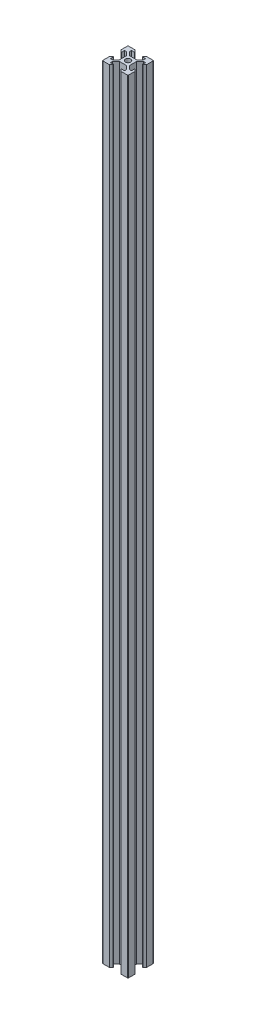
SolidWorks part; units mm, degrees
ref_plane "Front Plane" through (0, 0, 0) normal (0, 0, 1) x (1, 0, 0)
ref_plane "Top Plane" through (0, 0, 0) normal (0, 1, 0) x (1, 0, 0)
ref_plane "Right Plane" through (0, 0, 0) normal (1, 0, 0) x (0, 0, -1)
sketch "Sketch1" plane through (0, 0, 0) normal (1, 0, 0) x (0, 0, -1)
  line L0 (0, 0) -> (0, 609.6)
  dimension "D1" = 609.6
other "Vslot2020 2020(5)"
ref_plane "Plane5" through (0, 0, 0) normal (0, 1, 0) x (0, 0, 1)
sketch "Sketch2" plane through (0, 0, 0) normal (0, 1, 0) x (0, 0, 1)
  line L58 (13.9, 7.1491) -> (13.9, 12.8445)
  line L59 (13.9, 12.8445) -> (16.5585, 15.4922)
  line L60 (16.5585, 15.4922) -> (16.5507, 15.5)
  line L61 (16.5507, 15.5) -> (18.2, 15.5)
  line L62 (18.2, 15.5) -> (18.2, 13.12)
  line L63 (18.2, 13.12) -> (18.5344, 13.12)
  line L64 (18.5344, 13.12) -> (20, 14.58)
  line L65 (20, 14.58) -> (20, 19.5)
  line L66 (19.5, 20) -> (14.575, 20)
  line L67 (14.575, 20) -> (13.12, 18.545)
  line L68 (13.12, 18.545) -> (13.12, 18.2)
  line L69 (13.12, 18.2) -> (15.5, 18.2)
  line L70 (15.5, 18.2) -> (15.5, 16.555)
  line L71 (15.5, 16.555) -> (12.8341, 13.9)
  line L72 (12.8341, 13.9) -> (7.155, 13.9)
  line L73 (7.155, 13.9) -> (4.5, 16.555)
  line L74 (4.5, 16.555) -> (4.5, 18.2)
  line L75 (4.5, 18.2) -> (6.875, 18.2)
  line L76 (6.875, 18.2) -> (6.875, 18.545)
  line L77 (6.875, 18.545) -> (5.42, 20)
  line L78 (5.42, 20) -> (0.5, 20)
  line L79 (0, 19.5) -> (0, 14.58)
  line L80 (0, 14.58) -> (1.46, 13.12)
  line L81 (1.46, 13.12) -> (1.8, 13.12)
  line L82 (1.8, 13.12) -> (1.8, 15.5)
  line L83 (1.8, 15.5) -> (3.445, 15.5)
  line L84 (3.445, 15.5) -> (3.4393, 15.4943)
  line L85 (3.4393, 15.4943) -> (6.0943, 12.8393)
  line L86 (6.0943, 12.8393) -> (6.1, 12.845)
  line L87 (6.1, 12.845) -> (6.1, 7.1491)
  line L88 (6.1, 7.1491) -> (3.4393, 4.5)
  line L89 (3.4393, 4.5) -> (1.8, 4.5)
  line L90 (1.8, 4.5) -> (1.8, 6.88)
  line L91 (1.8, 6.88) -> (1.46, 6.88)
  line L92 (1.46, 6.88) -> (0, 5.42)
  line L93 (0, 5.42) -> (0, 0.5)
  line L94 (0.5, 0) -> (5.42, 0)
  line L95 (5.42, 0) -> (6.875, 1.455)
  line L96 (6.875, 1.455) -> (6.875, 1.8)
  line L97 (6.875, 1.8) -> (4.5, 1.8)
  line L98 (4.5, 1.8) -> (4.5, 3.4393)
  line L99 (4.5, 3.4393) -> (7.1583, 6.0861)
  line L100 (7.1583, 6.0861) -> (7.1445, 6.1)
  line L101 (7.1445, 6.1) -> (12.8546, 6.1)
  line L102 (12.8546, 6.1) -> (12.8412, 6.0865)
  line L103 (12.8412, 6.0865) -> (15.4997, 3.4375)
  line L104 (15.4997, 3.4375) -> (15.5, 3.4377)
  line L105 (15.5, 3.4377) -> (15.5, 1.8)
  line L106 (15.5, 1.8) -> (13.12, 1.8)
  line L107 (13.12, 1.8) -> (13.12, 1.455)
  line L108 (13.12, 1.455) -> (14.575, 0)
  line L109 (14.575, 0) -> (19.5, 0)
  line L110 (20, 0.5) -> (20, 5.42)
  line L111 (20, 5.42) -> (18.6069, 6.88)
  line L112 (18.6069, 6.88) -> (18.2, 6.88)
  line L113 (18.2, 6.88) -> (18.2, 4.5)
  line L114 (18.2, 4.5) -> (16.5585, 4.5)
  line L115 (16.5585, 4.5) -> (13.9, 7.1491)
  line L116 (13.9, 7.1491) -> (13.9, 12.8445)
  line L117 (13.9, 12.8445) -> (16.5585, 15.4922)
  line L118 (16.5585, 15.4922) -> (16.5507, 15.5)
  line L119 (16.5507, 15.5) -> (18.2, 15.5)
  line L120 (18.2, 15.5) -> (18.2, 13.12)
  line L121 (18.2, 13.12) -> (18.5344, 13.12)
  line L122 (18.5344, 13.12) -> (20, 14.58)
  line L123 (20, 14.58) -> (20, 19.5)
  line L124 (19.5, 20) -> (14.575, 20)
  line L125 (14.575, 20) -> (13.12, 18.545)
  line L126 (13.12, 18.545) -> (13.12, 18.2)
  line L127 (13.12, 18.2) -> (15.5, 18.2)
  line L128 (15.5, 18.2) -> (15.5, 16.555)
  line L129 (15.5, 16.555) -> (12.8341, 13.9)
  line L130 (12.8341, 13.9) -> (7.155, 13.9)
  line L131 (7.155, 13.9) -> (4.5, 16.555)
  line L132 (4.5, 16.555) -> (4.5, 18.2)
  line L133 (4.5, 18.2) -> (6.875, 18.2)
  line L134 (6.875, 18.2) -> (6.875, 18.545)
  line L135 (6.875, 18.545) -> (5.42, 20)
  line L136 (5.42, 20) -> (0.5, 20)
  line L137 (0, 19.5) -> (0, 14.58)
  line L138 (0, 14.58) -> (1.46, 13.12)
  line L139 (1.46, 13.12) -> (1.8, 13.12)
  line L140 (1.8, 13.12) -> (1.8, 15.5)
  line L141 (1.8, 15.5) -> (3.445, 15.5)
  line L142 (3.445, 15.5) -> (3.4393, 15.4943)
  line L143 (3.4393, 15.4943) -> (6.0943, 12.8393)
  line L144 (6.0943, 12.8393) -> (6.1, 12.845)
  line L145 (6.1, 12.845) -> (6.1, 7.1491)
  line L146 (6.1, 7.1491) -> (3.4393, 4.5)
  line L147 (3.4393, 4.5) -> (1.8, 4.5)
  line L148 (1.8, 4.5) -> (1.8, 6.88)
  line L149 (1.8, 6.88) -> (1.46, 6.88)
  line L150 (1.46, 6.88) -> (0, 5.42)
  line L151 (0, 5.42) -> (0, 0.5)
  line L152 (0.5, 0) -> (5.42, 0)
  line L153 (5.42, 0) -> (6.875, 1.455)
  line L154 (6.875, 1.455) -> (6.875, 1.8)
  line L155 (6.875, 1.8) -> (4.5, 1.8)
  line L156 (4.5, 1.8) -> (4.5, 3.4393)
  line L157 (4.5, 3.4393) -> (7.1583, 6.0861)
  line L158 (7.1583, 6.0861) -> (7.1445, 6.1)
  line L159 (7.1445, 6.1) -> (12.8546, 6.1)
  line L160 (12.8546, 6.1) -> (12.8412, 6.0865)
  line L161 (12.8412, 6.0865) -> (15.4997, 3.4375)
  line L162 (15.4997, 3.4375) -> (15.5, 3.4377)
  line L163 (15.5, 3.4377) -> (15.5, 1.8)
  line L164 (15.5, 1.8) -> (13.12, 1.8)
  line L165 (13.12, 1.8) -> (13.12, 1.455)
  line L166 (13.12, 1.455) -> (14.575, 0)
  line L167 (14.575, 0) -> (19.5, 0)
  line L168 (20, 0.5) -> (20, 5.42)
  line L169 (20, 5.42) -> (18.6069, 6.88)
  line L170 (18.6069, 6.88) -> (18.2, 6.88)
  line L171 (18.2, 6.88) -> (18.2, 4.5)
  line L172 (18.2, 4.5) -> (16.5585, 4.5)
  line L173 (16.5585, 4.5) -> (13.9, 7.1491)
  circle A0 centre (10, 10) radius 2.0746 construction
  circle A1 centre (10, 10) radius 2.0746
  arc A4 (20, 19.5) -> (19.5, 20) centre (19.5, 19.5) ccw
  arc A5 (0.5, 20) -> (0, 19.5) centre (0.5, 19.5) ccw
  arc A6 (0, 0.5) -> (0.5, 0) centre (0.5, 0.5) ccw
  arc A7 (19.5, 0) -> (20, 0.5) centre (19.5, 0.5) ccw
  arc A8 (20, 19.5) -> (19.5, 20) centre (19.5, 19.5) ccw
  arc A9 (0.5, 20) -> (0, 19.5) centre (0.5, 19.5) ccw
  arc A10 (0, 0.5) -> (0.5, 0) centre (0.5, 0.5) ccw
  arc A11 (19.5, 0) -> (20, 0.5) centre (19.5, 0.5) ccw
  point P16 (0, 0)
  dimension "D1" = 0
ref_plane "Plane6" through (0, 0, 9.9946) normal (0, 0, 1) x (1, 0, 0)
ref_plane "Plane7" through (9.997, 0, 0) normal (1, 0, 0) x (0, 0, -1)
